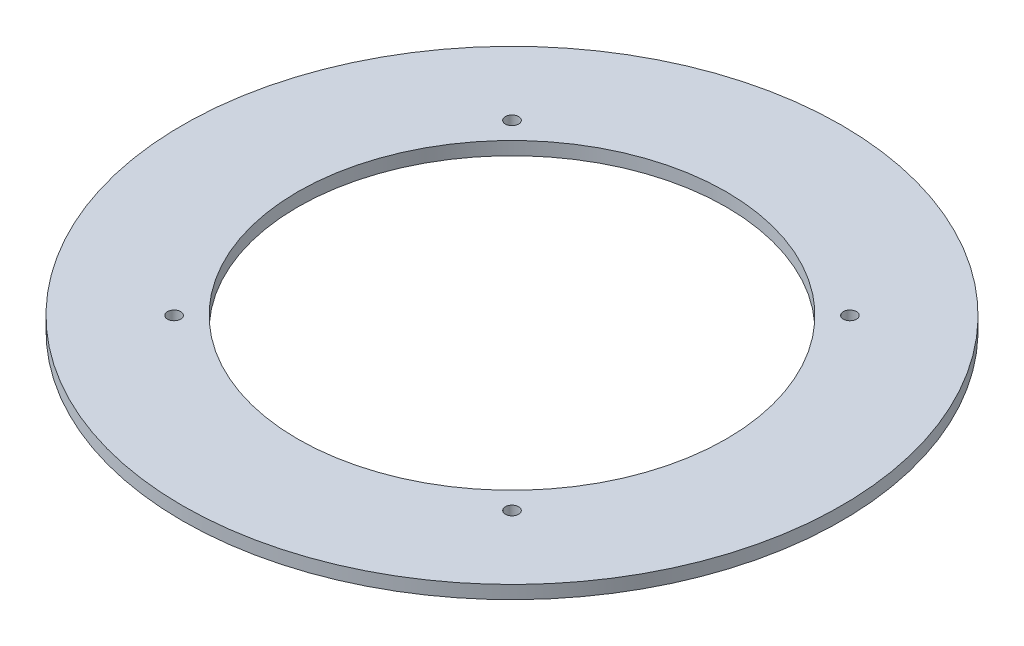
SolidWorks part; units mm, degrees
material "6061-T6 (SS)"
ref_plane "Front Plane" through (0, 0, 0) normal (0, 0, 1) x (1, 0, 0)
ref_plane "Top Plane" through (0, 0, 0) normal (0, 1, 0) x (1, 0, 0)
ref_plane "Right Plane" through (0, 0, 0) normal (1, 0, 0) x (0, 0, -1)
sketch "Sketch2" plane through (0, 0, 0) normal (0, 1, 0) x (1, 0, 0)
  line L0 (-100, 0) -> (100, 0) construction
  line L1 (-70.87, 70.551) -> (-70.87, -70.551) construction
  line L2 (0, 100) -> (0, -100) construction
  line L3 (70.87, 70.551) -> (70.87, -70.551) construction
  circle A0 centre (0, 0) radius 65
  circle A1 centre (0, 0) radius 100
  dimension "D1" = 130
  dimension "D2" = 200
  dimension "D4" = 141.74
extrude "Boss-Extrude1" add sketch "Sketch2" along normal blind 4
sketch "Sketch3" plane through (0, 4, 0) normal (0, 1, 0) x (1, 0, 0)
  line L0 (0, 100) -> (0, 65) construction
  circle A0 centre (0, 0) radius 82.5 construction
  circle A1 centre (0, 0) radius 100 construction
  circle A2 centre (0, 0) radius 65 construction
  point P10 (0, 82.5)
sketch "Sketch4" plane through (0, 0, 0) normal (0, -1, 0) x (1, 0, 0)
  line L0 (0, 100) -> (0, 65) construction
  line L1 (0, 65) -> (0, 0) construction
  line L2 (0, 0) -> (0, -65) construction
  line L3 (0, -65) -> (0, -100) construction
  line L4 (-100, 0) -> (-65, 0) construction
  line L5 (-65, 0) -> (0, 0) construction
  line L6 (0, 0) -> (65, 0) construction
  line L7 (65, 0) -> (100, 0) construction
  circle A0 centre (0, 0) radius 100 construction
  circle A1 centre (0, 0) radius 65 construction
sketch "Sketch5" plane through (0, 0, 0) normal (0, -1, 0) x (1, 0, 0)
  line L0 (0, 0) -> (-45.9619, 45.9619) construction
  line L1 (-65, 0) -> (0, 0) construction
  line L2 (0, 0) -> (45.9619, -45.9619) construction
  line L3 (45.9619, -45.9619) -> (70.7107, -70.7107) construction
  line L4 (-45.9619, 45.9619) -> (-70.7107, 70.7107) construction
  line L5 (0, 0) -> (-45.9619, -45.9619) construction
  line L6 (-45.9619, -45.9619) -> (-70.7107, -70.7107) construction
  line L7 (0, 0) -> (45.9619, 45.9619) construction
  line L8 (45.9619, 45.9619) -> (70.7107, 70.7107) construction
  circle A0 centre (0, 0) radius 65 construction
  circle A1 centre (-51.2652, 51.2652) radius 2
  circle A4 centre (0, 0) radius 100 construction
  circle A5 centre (51.2652, -51.2652) radius 2
  circle A6 centre (-51.2652, -51.2652) radius 2
  circle A7 centre (51.2652, 51.2652) radius 2
  dimension "D2" = 4
  dimension "D3" = 145
  dimension "D4" = 4
  dimension "D5" = 145
  dimension "D1" = 45
extrude "Cut-Extrude1" cut sketch "Sketch5" against normal through all
